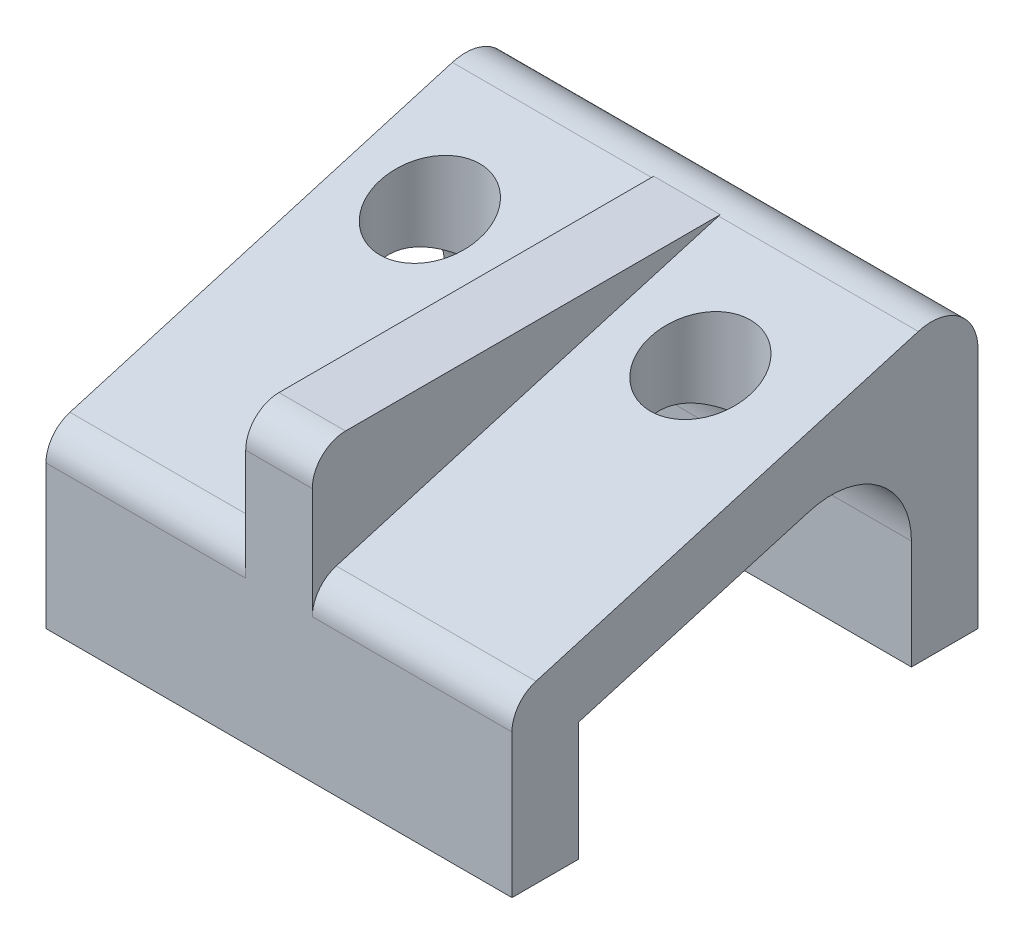
SolidWorks part; units mm, degrees
ref_plane "Front Plane" through (0, 0, 0) normal (0, 0, 1) x (1, 0, 0)
ref_plane "Top Plane" through (0, 0, 0) normal (0, 1, 0) x (1, 0, 0)
ref_plane "Right Plane" through (0, 0, 0) normal (1, 0, 0) x (0, 0, -1)
sketch "Sketch2" plane through (0, 0, 0) normal (1, 0, 0) x (0, 0, -1)
  line L0 (0, 25.2951) -> (0, 0)
  line L1 (0, 0) -> (10, 0)
  line L2 (10, 0) -> (10, 17.8318)
  line L3 (10, 17.8318) -> (44.6475, 27.9129)
  line L4 (60, 16.3907) -> (60, 0)
  line L5 (60, 0) -> (70, 0)
  line L6 (70, 0) -> (70, 36.419)
  line L7 (61.0359, 43.1378) -> (0, 25.2951)
  arc A0 (60, 16.3907) -> (44.6475, 27.9129) centre (48, 16.3907) ccw
  arc A1 (70, 36.419) -> (61.0359, 43.1378) centre (63, 36.419) ccw
  point P0 (30.5179, 34.2164)
  point P3 (0, 21.9335)
  point P12 (0, 19.1973)
  dimension "D5" = 12
  dimension "D6" = 7
  dimension "D1" = 70
  dimension "D2" = 10
  dimension "D3" = 10
  dimension "D4" = 10
extrude "Boss-Extrude1" add sketch "Sketch2" along normal mid plane 70
sketch "Sketch4" plane through (0, 0, 0) normal (0, 0, 1) x (1, 0, 0)
  line L0 (-4.9996, 25.2951) -> (4.9996, 25.2951)
  line L3 (35, 25.2951) -> (-35, 25.2951) construction
  line L4 (4.9996, 25.2951) -> (4.9996, 43.2081)
  line L5 (4.9996, 43.2081) -> (-4.9996, 43.2081)
  line L6 (-4.9996, 43.2081) -> (-4.9996, 25.2951)
  point P6 (0, 25.2951)
extrude "Boss-Extrude2" add sketch "Sketch4" against normal up to next
sketch "Sketch6" plane through (0, 0, 0) normal (0, 1, 0) x (1, 0, 0)
  circle A0 centre (18.36, 44.9389) radius 7.5
  circle A1 centre (-22.2768, 44.9389) radius 7.5
  point P4 (0, 0)
  dimension "D1" = 15
  dimension "D2" = 15
extrude "Cut-Extrude1" cut sketch "Sketch6" along normal up to surface (36.2396 mm away)
fillet "Fillet2" radius 5 3 edges at (0, 43.2081, 0) (19.9998, 25.2951, 0) (-19.9998, 25.2951, 0)
